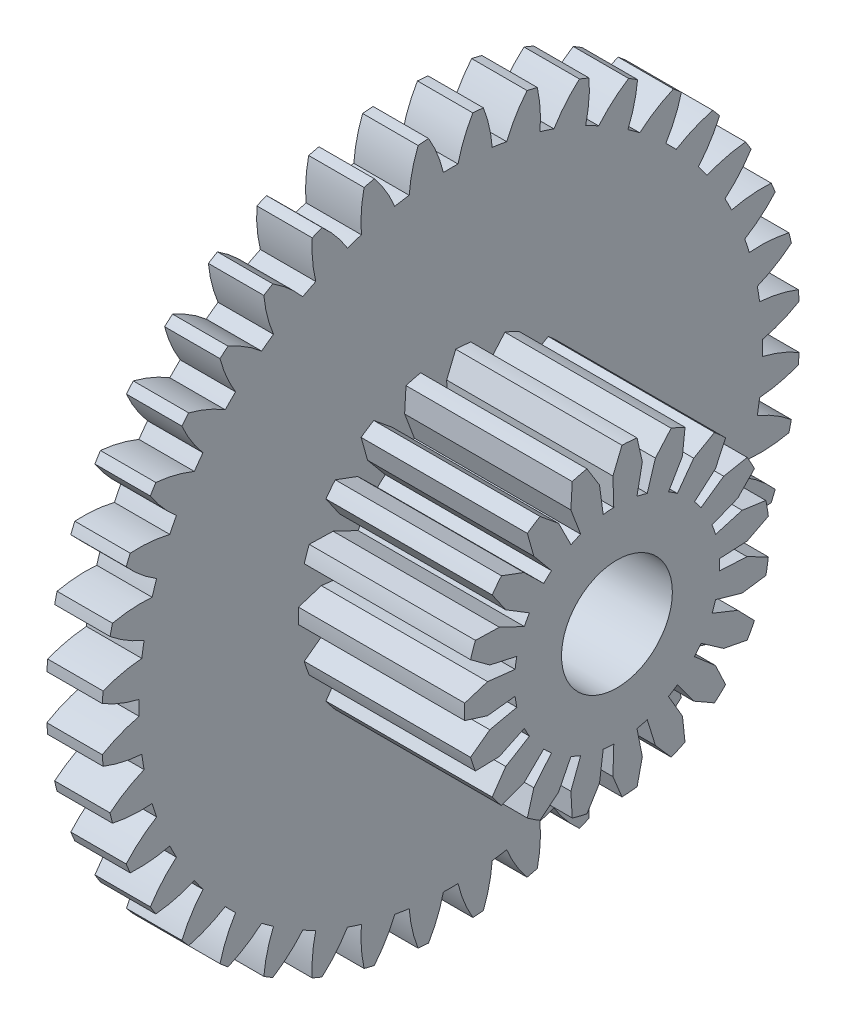
SolidWorks part; units mm, degrees
material "ABS PC"
ref_plane "Plane1" through (0, 0, 0) normal (0, 0, 1) x (1, 0, 0)
ref_plane "Plane2" through (0, 0, 0) normal (0, 1, 0) x (1, 0, 0)
ref_plane "Plane3" through (0, 0, 0) normal (1, 0, 0) x (0, 0, -1)
sketch "HoldingSke" plane through (0, 0, 0) normal (0, 1, 0) x (1, 0, 0)
  line L0 (0, 0) -> (2.5535, -2.1426)
  line L1 (-15, 0) -> (100, 0) construction
  line L2 (0, 0) -> (-2.1039, 2.3779)
  line L3 (0, 0) -> (-11.863, 4.5341)
  line L4 (0, 0) -> (6.6156, 5.5511)
  line L5 (0, 0) -> (-46.8476, -17.4728)
  line L6 (0, 0) -> (-0.829, -0.5593)
  line L7 (-2.1039, 2.3779) -> (8.6586, 51.2059)
  line L8 (-76.2, 54.61) -> (-75.9, 54.61)
  line L9 (-71.009, 38.7566) -> (-53.1078, 45.2721)
  line L10 (-76.2, 71.12) -> (104.1128, 71.12)
  line L11 (0, 0) -> (-1, 0)
  line L12 (-76.2, 101.6) -> (-76.19, 101.6)
  line L13 (24.9733, 27.94) -> (52.9518, 28.4284)
  line L14 (24.9733, 27.94) -> (24.9743, 27.94)
  line L15 (24.9733, 27.94) -> (100.4006, 29.5858)
  line L16 (-63.627, -0.3) -> (-12.827, -0.3)
  circle A0 centre (0, 0) radius 1
  circle A1 centre (0, 0) radius 5.624
  circle A2 centre (0, 0) radius 37.5
  circle A3 centre (0, 0) radius 1
  dimension "MHD" = 11.248
  dimension "Hub_dia" = 75
  dimension "Bore" = 2
  dimension "MBD" = 2
  dimension "Num_teeth" = 40
  dimension "Pitch" = 3.3333
  dimension "Overall_len" = 50
  dimension "Show_teeth" = 40
  dimension "Thickness" = 1
  dimension "OAL" = 50.0001
  dimension "T_dim" = 0.3
  dimension "Ap" = 20
  dimension "H" = 19.05
  dimension "Pitch_radius" = 180.3128
  dimension "Width" = 1
  dimension "Backlash" = 0.01
  dimension "Addendum_fac" = 1
  dimension "Dedendum_fac" = 1.25
  dimension "Clearance_fac" = 0.25
  dimension "Dedendum_add" = 0.001
  dimension "Module" = 0.3
sketch "BasProSke" plane through (0, 0, 0) normal (0, 1, 0) x (1, 0, 0)
  line L0 (-10, 0) -> (60, 0) construction
  line L1 (0, 0) -> (0, 6.3)
  line L2 (0, 0) -> (1, 0)
  line L3 (1, 0) -> (1, 6.3)
  line L4 (1, 6.3) -> (0, 6.3)
  dimension "Thickness" = 1
  dimension "Diameter" = 12.6
revolve "Base-Revolve" add sketch "BasProSke" angle 360 about L0
sketch "TooCutSke" plane through (0, 0, 0) normal (1, 0, 0) x (0, 0, -1)
  line L1 (0, 0) -> (0, 107) construction
  line L2 (0, 0) -> (-0.2531, 5.9947) construction
  line L3 (0, 0) -> (-0.9409, 11.9551) construction
  line L4 (-0.2531, 5.9947) -> (-0.4704, 5.9776) construction
  arc A0 (0.1321, 5.6224) -> (-0.1321, 5.6224) centre (0, 0) ccw
  arc A1 (0.4141, 6.3118) -> (-0.4141, 6.3118) centre (0, 0) ccw
  circle A2 centre (0, 0) radius 6 construction
  circle A3 centre (0, 0) radius 5.6382 construction
  arc A4 (-0.1321, 5.6224) -> (-0.4141, 6.3118) centre (-2.4676, 5.0695) ccw
  arc A5 (0.4141, 6.3118) -> (0.1321, 5.6224) centre (2.4676, 5.0695) ccw
  dimension "Root_dia" = 11.248
  dimension "Overcut_dia" = 12.6508
  dimension "Pitch_dia" = 12
  dimension "Base_dia" = 11.2763
  dimension "Flank_rad" = 2.4
  dimension "Half_ang" = 4.5
  dimension "Half_CT" = 0.2181
extrude "ToothCut" cut sketch "TooCutSke" along normal through all
fillet "Breaks" [suppressed] radius 0.006
fillet "RootFillets" [suppressed] radius 0.076
pattern_circular "TeethCuts" count 40 every 9 about axis through (-10, 0, 0) along (1, 0, 0) of "ToothCut", "RootFillets", "Breaks"
sketch "HubNeaOneSke" plane through (0, 0, 0) normal (-1, 0, 0) x (0, 0, 1)
  circle A0 centre (0, 0) radius 5.624
  dimension "Diameter" = 11.248
extrude "HubNearOne" [suppressed] add sketch "HubNeaOneSke" along normal blind 49.0001
sketch "HubNeaBotSke" plane through (0, 0, 0) normal (-1, 0, 0) x (0, 0, 1)
  circle A0 centre (0, 0) radius 5.624
  dimension "Diameter" = 11.248
extrude "HubNearBoth" [suppressed] add sketch "HubNeaBotSke" along normal blind 24.5
ref_plane "FarPln" through (1, 0, 0) normal (1, 0, 0) x (0, 0, -1)
sketch "HubFarSke" plane through (1, 0, 0) normal (1, 0, 0) x (0, 0, -1)
  circle A0 centre (0, 0) radius 5.624
  dimension "Diameter" = 11.248
extrude "HubFar" [suppressed] add sketch "HubFarSke" along normal blind 24.5
sketch "BorSke" plane through (0, 0, 0) normal (1, 0, 0) x (0, 0, -1)
  circle A0 centre (0, 0) radius 1
  dimension "Diameter" = 2
extrude "Bore" cut sketch "BorSke" along normal mid plane 100.0001
sketch "KeySke" plane through (0, 0, 0) normal (1, 0, 0) x (0, 0, -1)
  line L0 (-0.4, 0) -> (-0.4, 1.3)
  line L1 (-0.4, 1.3) -> (0.4, 1.3)
  line L2 (0.4, 1.3) -> (0.4, 0)
  line L3 (0, 0) -> (0, 34) construction
  line L4 (-0.4, 0) -> (0.4, 0)
  dimension "Offset" = 1.3
  dimension "Width" = 0.8
extrude "Keyway" [suppressed] cut sketch "KeySke" along normal mid plane 100.0001
pattern_circular "Keyway2" [suppressed] count 2 every 90 about axis through (-10, 0, 0) along (1, 0, 0)
sketch "Schizzo2" plane through (1, 0, 0) normal (1, 0, 0) x (0, 0, -1)
  circle A0 centre (0, 0) radius 1
  circle A1 centre (0, 0) radius 2.75
  circle A2 centre (0, 0) radius 1 construction
  dimension "D1" = 5.5
extrude "Estrusione-Estrusione1" add sketch "Schizzo2" along normal blind 3
sketch "Schizzo1" plane through (4, 0, 0) normal (1, 0, 0) x (0, 0, -1)
  line L0 (0, 0) -> (2.3, 0) construction
  line L1 (0, 0) -> (2.3469, 0.1215) construction
  line L2 (0, 0) -> (2.3469, -0.1215) construction
  line L3 (3.1401, 0.8301) -> (3.1401, -0.8301) construction
  line L4 (2.3469, 0.1215) -> (1.8475, 0.0956)
  line L5 (2.3469, -0.1215) -> (1.8475, -0.0956)
  line L6 (2.3469, 0.1215) -> (2.7316, 0.3172)
  line L7 (2.3469, -0.1215) -> (2.7316, -0.3172)
  line L9 (2.3469, -0.1215) -> (2.3469, 0.1215) construction
  arc A1 (1.8475, -0.0956) -> (1.8475, 0.0956) centre (0, 0) ccw
  circle A2 centre (0, 0) radius 1 construction
  circle A5 centre (0, 0) radius 2.75
  arc A6 (2.7316, -0.3172) -> (2.7316, 0.3172) centre (0, 0) ccw
  spline S0 degree 4 poles (2.3469, 0.1215) (2.3485, 0.1216) (2.353, 0.1219) (2.367, 0.1237) (2.3942, 0.1292) (2.4273, 0.1389) (2.4646, 0.1526) (2.4999, 0.168) (2.5296, 0.1824) (2.5588, 0.1979) (2.5874, 0.2144) (2.6214, 0.2355) (2.6614, 0.2625) (2.7069, 0.2964) (2.7568, 0.3376) (2.8057, 0.3823) (2.8523, 0.4286) (2.8973, 0.4777) (2.9396, 0.5271) (2.9812, 0.5807) (3.0186, 0.6314) (3.0579, 0.6906) (3.0889, 0.7392) (3.127, 0.8057) (3.1487, 0.8457) (3.173, 0.8933) (3.1833, 0.9148) (3.1896, 0.9281) knots 0 0 0 0 0 0.005377 0.015084 0.04661 0.092111 0.119476 0.146842 0.174209 0.201575 0.228941 0.256307 0.307035 0.361767 0.4165 0.471232 0.525964 0.580697 0.635429 0.690161 0.744894 0.799626 0.854358 0.909091 0.954545 1 1 1 1 1 construction
  spline S1 degree 4 poles (2.3469, 0.1215) (2.3485, 0.1216) (2.353, 0.1219) (2.367, 0.1237) (2.3942, 0.1292) (2.4273, 0.1389) (2.4646, 0.1526) (2.4999, 0.168) (2.5296, 0.1824) (2.5588, 0.1979) (2.5874, 0.2144) (2.6214, 0.2355) (2.6614, 0.2625) (2.7069, 0.2964) (2.7568, 0.3376) (2.8057, 0.3823) (2.8523, 0.4286) (2.8973, 0.4777) (2.9396, 0.5271) (2.9812, 0.5807) (3.0186, 0.6314) (3.0579, 0.6906) (3.0889, 0.7392) (3.1188, 0.7912) (3.1329, 0.8169) (3.1401, 0.8301) knots 0 0 0 0 0 0.005377 0.015084 0.04661 0.092111 0.119476 0.146842 0.174209 0.201575 0.228941 0.256307 0.307035 0.361767 0.4165 0.471232 0.525964 0.580697 0.635429 0.690161 0.744894 0.799626 0.854358 0.909091 0.909091 0.909091 0.909091 0.909091 construction
  spline S2 degree 4 poles (2.3469, -0.1215) (2.3485, -0.1216) (2.353, -0.1219) (2.367, -0.1237) (2.3942, -0.1292) (2.4273, -0.1389) (2.4646, -0.1526) (2.4999, -0.168) (2.5296, -0.1824) (2.5588, -0.1979) (2.5874, -0.2144) (2.6214, -0.2355) (2.6614, -0.2625) (2.7069, -0.2964) (2.7568, -0.3376) (2.8057, -0.3823) (2.8523, -0.4286) (2.8973, -0.4777) (2.9396, -0.5271) (2.9812, -0.5807) (3.0186, -0.6314) (3.0579, -0.6906) (3.0889, -0.7392) (3.1188, -0.7912) (3.1329, -0.8169) (3.1401, -0.8301) knots 0 0 0 0 0 0.005377 0.015084 0.04661 0.092111 0.119476 0.146842 0.174209 0.201575 0.228941 0.256307 0.307035 0.361767 0.4165 0.471232 0.525964 0.580697 0.635429 0.690161 0.744894 0.799626 0.854358 0.909091 0.909091 0.909091 0.909091 0.909091 construction
  dimension "D1" = 3.7
  dimension "D2" = 2.963
  dimension "D3" = 2.3
  dimension "D4" = 0.5
  dimension "D5" = 0
extrude "Taglio-Estrusione2" cut sketch "Schizzo1" against normal up to surface (3 mm away) up to face at (1, 0, 0)
pattern_circular "RipetizioneCircolare1" count 19 over 360 about axis through (0, 0, 0) along (1, 0, 0) of "Taglio-Estrusione2"
equation "' \"Module@HoldingSke\" = 6.35"
equation "' \"Num_teeth@HoldingSke\" = 12"
equation "' \"Ap@HoldingSke\" =  20"
equation "' \"Ap@HoldingSke\" = 20"
equation "' \"Width@HoldingSke\" = 0.5 * 25.4"
equation "' \"Hub_dia@HoldingSke\"= 1 * 25.4"
equation "' \"Hub_dia@HoldingSke\" = 1 * 25.4"
equation "' \"Overall_len@HoldingSke\" = 1.0 * 25.4"
equation "' \"Bore@HoldingSke\" = 0.75 * 25.4"
equation "' \"T_dim@HoldingSke\" = 0.1 * 25.4"
equation "' \"Width@KeySke\" = 0.25 * 25.4"
equation "' \"Show_teeth@HoldingSke\" = 13"
equation "' \"Backlash@HoldingSke\" = 0.009 * 25.4"
equation "' \"Addendum_fac@HoldingSke\" = 1.0"
equation "' \"Dedendum_fac@HoldingSke\" = 1.25"
equation "' \"Dedendum_add@HoldingSke\" = 0.00005 * 25.4"
equation "' \"Clearance_fac@HoldingSke\" = 0.25"
equation "\"Pitch@HoldingSke\" = 1 / \"Module@HoldingSke\""
equation "\"Overcut_dia@TooCutSke\" = (\"Num_teeth@HoldingSke\" + 2 * \"Addendum_fac@HoldingSke\") / \"Pitch@HoldingSke\" + 0.002 * 25.4"
equation "\"Pitch_dia@TooCutSke\" = \"Num_teeth@HoldingSke\" / \"Pitch@HoldingSke\""
equation "\"Base_dia@TooCutSke\" = \"Num_teeth@HoldingSke\" / \"Pitch@HoldingSke\" * cos((\"Ap@HoldingSke\"  * 3.14159265 / 180))"
equation "\"Root_dia@TooCutSke\" = (\"Num_teeth@HoldingSke\" + 2) / \"Pitch@HoldingSke\" - 2 * (\"Addendum_fac@HoldingSke\" + \"Dedendum_fac@HoldingSke\") / \"Pitch@HoldingSke\" - \"Dedendum_add@HoldingSke\" * 2"
equation "\"Half_ang@TooCutSke\" = 180 / \"Num_teeth@HoldingSke\""
equation "\"Half_CT@TooCutSke\" = \"Num_teeth@HoldingSke\" / \"Pitch@HoldingSke\" * sin((3.14159265 / 2 / \"Num_teeth@HoldingSke\")) / 2 - 7 * \"Backlash@HoldingSke\" / 4"
equation "\"Flank_rad@TooCutSke\" = \"Num_teeth@HoldingSke\" / \"Pitch@HoldingSke\" / 5"
equation "\"Radius@RootFillets\" = \"Clearance_fac@HoldingSke\" / \"Pitch@HoldingSke\" + \"Dedendum_add@HoldingSke\""
equation "\"Break_rad@Breaks\" = 0.02 / \"Pitch@HoldingSke\""
equation "\"Thickness@HoldingSke\" = \"Width@HoldingSke\""
equation "\"OAL@HoldingSke\" = \"Thickness@HoldingSke\""
equation "\"MHD@HoldingSke\" = (\"Num_teeth@HoldingSke\" + 2) / \"Pitch@HoldingSke\" - 2 * (\"Addendum_fac@HoldingSke\" + \"Dedendum_fac@HoldingSke\")  / \"Pitch@HoldingSke\" - \"Dedendum_add@HoldingSke\" * 2"
equation "\"MBD@HoldingSke\" = (\"Num_teeth@HoldingSke\" + 2) / \"Pitch@HoldingSke\" - 2 * (\"Addendum_fac@HoldingSke\" + \"Dedendum_fac@HoldingSke\")  / \"Pitch@HoldingSke\" - \"Dedendum_add@HoldingSke\" * 2 - 0.002 * 25.4"
equation "\"MHD@HoldingSke\" = ((sgn( \"MHD@HoldingSke\" - \"Hub_dia@HoldingSke\" )-1)*( \"MHD@HoldingSke\" - \"Hub_dia@HoldingSke\" ))/-2+ \"Hub_dia@HoldingSke\""
equation "\"MBD@HoldingSke\" = ((sgn( \"MBD@HoldingSke\" - \"Bore@HoldingSke\" )-1)*( \"MBD@HoldingSke\" - \"Bore@HoldingSke\" ))/-2+ \"Bore@HoldingSke\""
equation "\"OAL@HoldingSke\" = ((sgn( \"OAL@HoldingSke\" - \"Overall_len@HoldingSke\" )+1)*( \"OAL@HoldingSke\" - \"Overall_len@HoldingSke\" ))/2 + \"Overall_len@HoldingSke\" + 0.000002 * 25.4"
equation "\"Num_teeth@TeethCuts\" = int( \"Show_teeth@HoldingSke\" ) + 1"
equation "\"Num_teeth@TeethCuts\" = ((sgn( \"Num_teeth@TeethCuts\" - \"Num_teeth@HoldingSke\" )-1)*( \"Num_teeth@TeethCuts\" - \"Num_teeth@HoldingSke\" ))/-2+ \"Num_teeth@HoldingSke\""
equation "\"Num_teeth@TeethCuts\" = ((sgn( \"Num_teeth@TeethCuts\" - 2.0)+1)*( \"Num_teeth@TeethCuts\" - 2.0))/2 +2.0"
equation "\"Angle@TeethCuts\" = 360.0 / \"Num_teeth@HoldingSke\""
equation "\"Diameter@BasProSke\" = (\"Num_teeth@HoldingSke\" + 2 * \"Addendum_fac@HoldingSke\") / \"Pitch@HoldingSke\""
equation "\"Thickness@BasProSke\"  = \"Thickness@HoldingSke\""
equation "' \"Fillet_rad@BasProSke\" =  \"Thickness@HoldingSke\" * 0.05"
equation "' \"Fillet_rad@BasProSke\" = \"Thickness@HoldingSke\" * 0.05"
equation "\"MHD@HoldingSke\" = ((sgn( \"MHD@HoldingSke\" - \"Root_dia@TooCutSke\" )-1)*( \"MHD@HoldingSke\" - \"Root_dia@TooCutSke\" ))/-2+ \"Root_dia@TooCutSke\""
equation "\"Diameter@HubNeaOneSke\" = \"MHD@HoldingSke\""
equation "\"Length@HubNearOne\" = \"OAL@HoldingSke\" - \"Thickness@BasProSke\""
equation "\"Diameter@HubNeaBotSke\" = \"MHD@HoldingSke\""
equation "\"Length@HubNearBoth\" = ( \"OAL@HoldingSke\" - \"Thickness@BasProSke\" ) / 2.0"
equation "\"Thickness@FarPln\" = \"Thickness@BasProSke\""
equation "\"Diameter@HubFarSke\" = \"MHD@HoldingSke\""
equation "\"Length@HubFar\" = ( \"OAL@HoldingSke\" - \"Thickness@BasProSke\" ) / 2.0"
equation "\"Diameter@BorSke\" = \"MBD@HoldingSke\""
equation "\"D1@Bore\" = \"OAL@HoldingSke\" * 2.0"
equation "\"D1@Keyway\" = \"OAL@HoldingSke\" * 2.0"
equation "\"Offset@KeySke\" = \"T_dim@HoldingSke\" + \"MBD@HoldingSke\" / 2.0"
